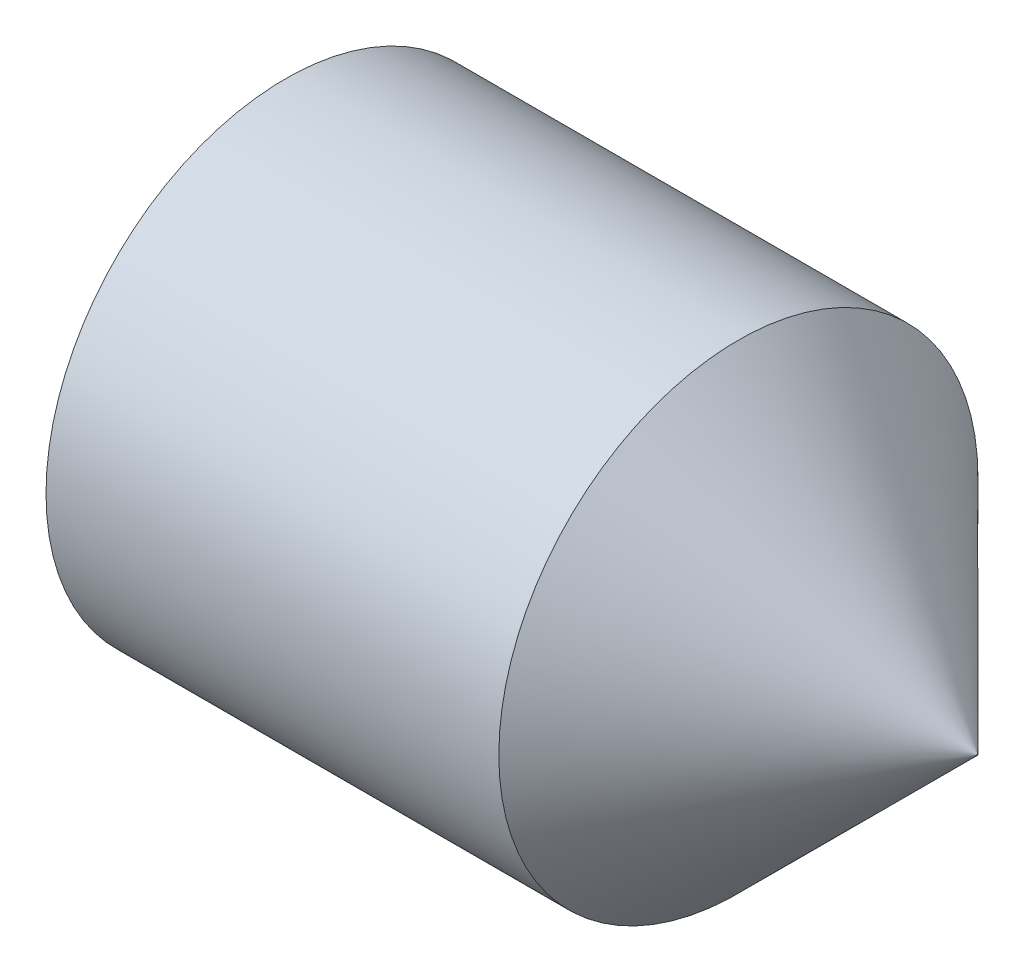
SolidWorks part; units mm, degrees
ref_plane "Plane1" through (0, 0, 0) normal (0, 0, 1) x (1, 0, 0)
ref_plane "Plane2" through (0, 0, 0) normal (0, 1, 0) x (1, 0, 0)
ref_plane "Plane3" through (0, 0, 0) normal (1, 0, 0) x (0, 0, -1)
sketch "BodySke" plane through (0, 0, 0) normal (0, 0, 1) x (1, 0, 0)
  line L0 (0, 0) -> (0, 1.61)
  line L1 (0, 1.61) -> (0.2252, 2)
  line L2 (0.2252, 2) -> (4.005, 2)
  line L3 (6, 0) -> (6, 0.005)
  line L4 (6, 0) -> (0, 0)
  line L5 (-12.7, 0) -> (88.9, 0) construction
  line L6 (6, 0.005) -> (4.005, 2)
  line L7 (0.7, 15.875) -> (0.7, -3.175) construction
  line L8 (0, -1.61) -> (0.2252, -2) construction
  line L9 (6, -0.005) -> (4.005, -2) construction
  dimension "Cone_ang" = 90
  dimension "Length" = 6
  dimension "Diameter" = 4
  dimension "Drive_ch_ang" = 60
  dimension "Minor_dia" = 3.22
  dimension "Advance" = 0.7
  dimension "Tip_dia" = 0.01
revolve "BaseBody" add sketch "BodySke" angle 360 about L5
cosmetic thread "ThreadCosmetic" [suppressed] parameters "Thread_minor"=3.22
sketch "Sketch2" plane through (0, 0, 0) normal (-1, 0, 0) x (0, 0, 1)
  line L0 (0.5774, 1) -> (-0.5774, 1)
  line L1 (-0.5774, 1) -> (-1.1547, 0)
  line L2 (0.5774, 1) -> (1.1547, 0)
  line L3 (0.5774, -1) -> (1.1547, 0)
  line L4 (0.5774, -1) -> (-0.5774, -1)
  line L5 (-0.5774, -1) -> (-1.1547, 0)
  dimension "Hex_size" = 2
  dimension "D2" = 1
  dimension "D3" = 1
extrude "Hex" cut sketch "Sketch2" against normal blind 2.3
sketch "Sketch4" plane through (0, 4.7709, -0.5249) normal (-1, 0, 0) x (0, 0, 1)
  line L0 (0.5249, -4.7709) -> (1.7694, -4.7709)
  line L1 (0.5249, -4.7709) -> (6.6732, -1.2211) construction
  line L2 (0.5249, -4.7709) -> (1.1471, -3.6931)
  line L3 (1.5335, -4.5113) -> (1.7149, -4.4066)
  line L4 (1.254, -4.0272) -> (1.4354, -3.9225)
  arc A0 (1.5335, -4.5113) -> (1.254, -4.0272) centre (0.5249, -4.7709) ccw
  arc A1 (1.7694, -4.7709) -> (1.7149, -4.4066) centre (0.5249, -4.7709) ccw
  arc A2 (1.1471, -3.6931) -> (1.4354, -3.9225) centre (0.5249, -4.7709) cw
  circle A3 centre (0.5249, -4.7709) radius 1.0415 construction
  circle A4 centre (0.5249, -4.7709) radius 1.2445 construction
  dimension "D1" = 30
  dimension "Spline_n_dim" = 2.083
  dimension "Spline_m_dim" = 2.489
  dimension "Spline_a_dim" = 60
  dimension "D3" = 0.2795
  dimension "Spline_p_dim" = 0.559
extrude "Spline6" [suppressed] cut sketch "Sketch4" against normal blind 2
pattern_circular "CirPattern1" [suppressed] count 6 every 60 about axis through (-12.7, 0, 0) along (1, 0, 0)
sketch "Sketch5" plane through (0, 1.4735, 6.925) normal (-1, 0, 0) x (0, 0, 1)
  line L0 (-6.925, -1.4735) -> (-5.6805, -1.4735)
  line L1 (-6.925, -1.4735) -> (-1.9049, 3.5466) construction
  line L2 (-6.925, -1.4735) -> (-6.925, -0.229)
  line L3 (-5.991, -0.9347) -> (-5.8699, -0.8136)
  line L4 (-6.3862, -0.5394) -> (-6.2652, -0.4183)
  line L5 (-6.3862, -0.5394) -> (-5.991, -0.9347)
  arc A1 (-5.6805, -1.4735) -> (-5.8699, -0.8136) centre (-6.925, -1.4735) ccw
  arc A2 (-6.925, -0.229) -> (-6.2652, -0.4183) centre (-6.925, -1.4735) cw
  circle A3 centre (-6.925, -1.4735) radius 1.0415 construction
  circle A4 centre (-6.925, -1.4735) radius 1.2445 construction
  dimension "D1" = 45
  dimension "Spline_n_dim" = 2.083
  dimension "Spline_m_dim" = 2.489
  dimension "Spline_a_dim" = 90
  dimension "D3" = 0.2795
  dimension "Spline_p_dim" = 0.559
extrude "Spline4" [suppressed] cut sketch "Sketch5" against normal blind 2
pattern_circular "CirPattern2" [suppressed] count 4 every 90 about axis through (-12.7, 0, 0) along (1, 0, 0)
sketch "ThdSchSke" plane through (0, 0, 0) normal (0, 0, 1) x (1, 0, 0)
  line L0 (0.2252, -1.61) -> (-0.0479, -2)
  line L1 (0.2252, -1.61) -> (0.4982, -2)
  line L2 (0.4982, -2) -> (0.4982, -2.5)
  line L3 (-3.175, 0) -> (5.1513, 0) construction
  line L4 (0.2252, 2) -> (0.2252, -2) construction
  line L5 (0.4982, -2.5) -> (-0.0479, -2.5)
  line L6 (-0.0479, -2.5) -> (-0.0479, -2)
  dimension "Thread_minor" = 3.22
  dimension "Diameter" = 4
  dimension "SideAngle" = 55
  dimension "VeeAngle" = 70
  dimension "Overcut" = 5
revolve "ThreadSchematic" [suppressed] cut sketch "ThdSchSke" angle 360 about L3
pattern_linear "ThdSchPat" [suppressed]
equation "\"D2@Sketch2\" = \"Hex_size@Sketch2\" / 2"
equation "\"D3@Sketch2\" = \"Hex_size@Sketch2\" / 2"
equation "\"Thread_minor@ThreadCosmetic\" = \"Minor_dia@BodySke\""
equation "\"D1@Sketch4\" = \"Spline_a_dim@Sketch4\" / 2"
equation "\"D3@Sketch4\" = \"Spline_p_dim@Sketch4\" / 2"
equation "\"D2@CirPattern1\" = \"Spline_a_dim@Sketch4\""
equation "\"Num_teeth@CirPattern1\" = 360 / \"D2@CirPattern1\""
equation "\"Spline_a_dim@Sketch5\" = 90"
equation "\"Spline_p_dim@Sketch5\" = \"Spline_p_dim@Sketch4\""
equation "\"Spline_m_dim@Sketch5\" = \"Spline_m_dim@Sketch4\""
equation "\"Spline_n_dim@Sketch5\" = \"Spline_n_dim@Sketch4\""
equation "\"D1@Sketch5\" = \"Spline_a_dim@Sketch5\" / 2"
equation "\"D3@Sketch5\" = \"Spline_p_dim@Sketch5\" / 2"
equation "\"Key_eng@Spline4\" = \"Key_eng@Spline6\""
equation "\"Thread_minor@ThdSchSke\" = \"Thread_minor@ThreadCosmetic\""
equation "\"Diameter@ThdSchSke\" = \"Diameter@BodySke\""
equation "\"Overcut@ThdSchSke\" = \"Diameter@BodySke\" * 1.25"
equation "\"Num_threads@ThdSchPat\" = int( (\"Length@BodySke\" - ( ( ( \"Diameter@BodySke\" - \"Minor_dia@BodySke\" ) * 0.5 ) / tan( \"Drive_ch_ang@BodySke\" * 0.017453292 ) ) - ( ( \"Diameter@BodySke\" * 0.5 ) / tan( \"Cone_ang@BodySke\" * 0.008726646 ) ) ) / \"Advance@BodySke\" + 0.999 )  + 1"
equation "\"Num_threads@ThdSchPat\" = int( (\"Length@BodySke\" - ( ( ( \"Diameter@BodySke\" - \"Minor_dia@BodySke\" ) * 0.5 ) / tan( \"Drive_ch_ang@BodySke\" * 0.017453292 ) ) - ( (( \"Diameter@BodySke\" - \"Tip_dia@BodySke\") * 0.5 ) / tan( \"Cone_ang@BodySke\" * 0.008726646 ) ) ) / \"Advance@BodySke\" + 0.999 )  + 1"
equation "\"Advance@ThdSchPat\" = (\"Length@BodySke\" - ( ( ( \"Diameter@BodySke\" - \"Minor_dia@BodySke\" ) * 0.5 ) / tan( \"Drive_ch_ang@BodySke\" * 0.017453292 ) ) - ( ( \"Diameter@BodySke\" * 0.5 ) / tan( \"Cone_ang@BodySke\" * 0.008726646 ) ) ) /  (\"Num_threads@ThdSchPat\" - 1) 'relax it"
equation "\"Advance@ThdSchPat\" = (\"Length@BodySke\" - ( ( ( \"Diameter@BodySke\" - \"Minor_dia@BodySke\" ) * 0.5 ) / tan( \"Drive_ch_ang@BodySke\" * 0.017453292 ) ) - ( ( (\"Diameter@BodySke\" - \"Tip_dia@BodySke\") * 0.5 ) / tan( \"Cone_ang@BodySke\" * 0.008726646 ) ) ) /  (\"Num_threads@ThdSchPat\" - 1) 'relax it"
equation "' \"Num_threads@ThdSchPat\" = \"Num_threads@ThdSchPat\" - sgn( \"Num_threads@ThdSchPat\" - 1) '---chamfered tips only---"
